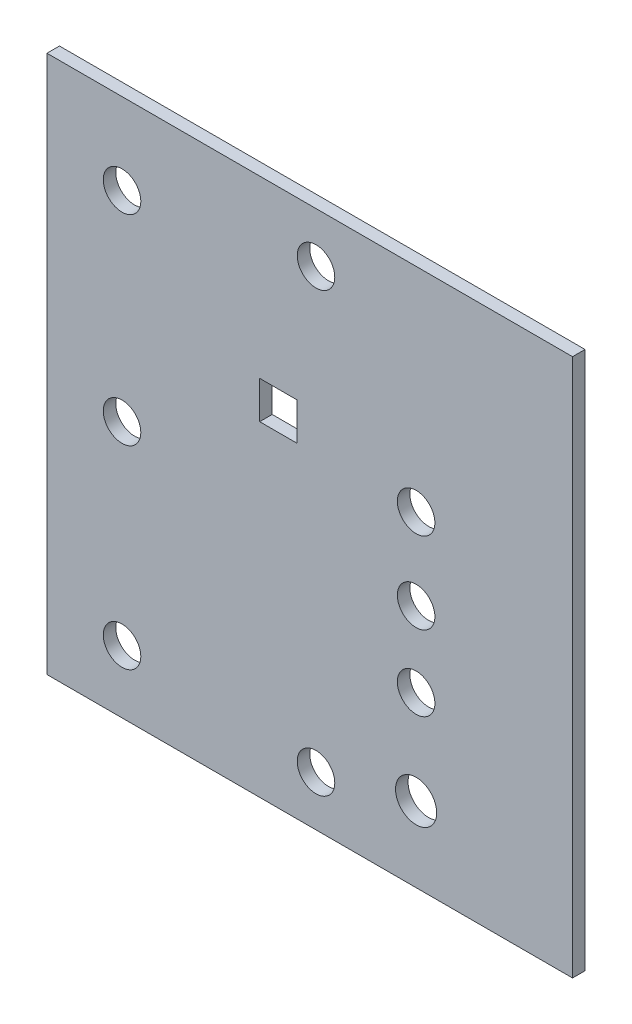
SolidWorks part; units mm, degrees
ref_plane "前基準面" through (0, 0, 0) normal (0, 0, 1) x (1, 0, 0)
ref_plane "上基準面" through (0, 0, 0) normal (0, 1, 0) x (1, 0, 0)
ref_plane "右基準面" through (0, 0, 0) normal (1, 0, 0) x (0, 0, -1)
sketch "草圖1" plane through (0, 0, 0) normal (0, 0, 1) x (1, 0, 0)
  line L1 (0, 0) -> (86, 0)
  line L2 (0, 0) -> (0, -86)
  line L3 (0, -86) -> (86, -86)
  line L4 (86, 0) -> (86, -86)
  dimension "D1" = 86
  dimension "D2" = 86
extrude "填料-伸長1" add sketch "草圖1" along normal blind 2 contours L1 L4 L3 L2
sketch "草圖2" plane through (0, 0, 2) normal (0, 0, 1) x (1, 0, 0)
  line L0 (0, 0) -> (86, 0) construction
  line L1 (0, 0) -> (0, -86) construction
  circle A0 centre (13, -13) radius 3
  dimension "D1" = 13
  dimension "D2" = 13
extrude "除料-伸長1" cut sketch "草圖2" against normal blind 3
sketch "草圖3" plane through (0, 0, 2) normal (0, 0, 1) x (1, 0, 0)
  line L0 (0, 0) -> (86, 0) construction
  line L1 (0, 0) -> (0, -86) construction
  circle A0 centre (13, -45) radius 3
  dimension "D1" = 45
  dimension "D2" = 13
extrude "除料-伸長2" cut sketch "草圖3" against normal blind 3 contours A0
sketch "草圖4" plane through (0, 0, 2) normal (0, 0, 1) x (1, 0, 0)
  line L0 (0, 0) -> (86, 0) construction
  line L1 (0, 0) -> (0, -86) construction
  circle A0 centre (13, -76) radius 3
  dimension "D1" = 76
  dimension "D2" = 13
extrude "除料-伸長3" cut sketch "草圖4" against normal blind 3 contours A0
sketch "草圖6" plane through (0, 0, 2) normal (0, 0, 1) x (1, 0, 0)
  line L0 (0, 0) -> (86, 0) construction
  line L1 (0, 0) -> (0, -86) construction
  circle A0 centre (44, -8) radius 3
  dimension "D1" = 8
  dimension "D2" = 44
extrude "除料-伸長4" cut sketch "草圖6" against normal blind 3
sketch "草圖7" plane through (0, 0, 2) normal (0, 0, 1) x (1, 0, 0)
  line L0 (0, -86) -> (86, -86) construction
  line L2 (0, 0) -> (0, -86) construction
  circle A0 centre (44, -78) radius 3
  dimension "D1" = 8
  dimension "D2" = 44
extrude "除料-伸長5" cut sketch "草圖7" against normal blind 3
sketch "草圖8" plane through (0, 0, 2) normal (0, 0, 1) x (1, 0, 0)
  line L0 (0, 0) -> (86, 0) construction
  line L1 (86, 0) -> (86, -86) construction
  circle A0 centre (60, -34) radius 3
  dimension "D1" = 34
  dimension "D2" = 26
extrude "除料-伸長6" cut sketch "草圖8" against normal blind 3
sketch "草圖9" plane through (0, 0, 2) normal (0, 0, 1) x (1, 0, 0)
  line L0 (0, 0) -> (86, 0) construction
  line L1 (86, 0) -> (86, -86) construction
  circle A0 centre (60, -47) radius 3
  dimension "D1" = 47
  dimension "D2" = 26
extrude "除料-伸長7" cut sketch "草圖9" against normal blind 3
sketch "草圖10" plane through (0, 0, 2) normal (0, 0, 1) x (1, 0, 0)
  line L0 (0, 0) -> (86, 0) construction
  line L1 (86, 0) -> (86, -86) construction
  circle A0 centre (60, -59) radius 3
  dimension "D1" = 59
  dimension "D2" = 26
extrude "除料-伸長8" cut sketch "草圖10" against normal blind 3
sketch "草圖11" plane through (0, 0, 2) normal (0, 0, 1) x (1, 0, 0)
  line L0 (0, 0) -> (86, 0) construction
  line L1 (86, 0) -> (86, -86) construction
  circle A0 centre (60, -74) radius 3.2908
  dimension "D1" = 74
  dimension "D2" = 26
extrude "除料-伸長9" cut sketch "草圖11" against normal blind 3
sketch "草圖12" plane through (0, 0, 2) normal (0, 0, 1) x (1, 0, 0)
  line L0 (0, 0) -> (0, -86) construction
  line L1 (35, -28) -> (41, -28)
  line L2 (35, -28) -> (35, -34)
  line L3 (35, -34) -> (41, -34)
  line L4 (41, -28) -> (41, -34)
  line L5 (0, 0) -> (86, 0) construction
  point P4 (35, -31)
  dimension "D1" = 6
  dimension "D2" = 6
  dimension "D3" = 35
  dimension "D4" = 28
extrude "除料-伸長10" cut sketch "草圖12" against normal blind 3
sketch "草圖13" plane through (0, 0, 2) normal (0, 0, 1) x (1, 0, 0)
  line L0 (0, -86) -> (86, -86) construction
  line L1 (86, 0) -> (85, 0)
  line L2 (86, 0) -> (86, -86)
  line L3 (86, -86) -> (85, -86)
  line L4 (85, 0) -> (85, -86)
  line L6 (0, 0) -> (1, 0)
  line L7 (0, 0) -> (0, -86)
  line L8 (0, -86) -> (1, -86)
  line L9 (1, 0) -> (1, -86)
  dimension "D1" = 1
  dimension "D2" = 1
extrude "除料-伸長11" cut sketch "草圖13" against normal blind 3
